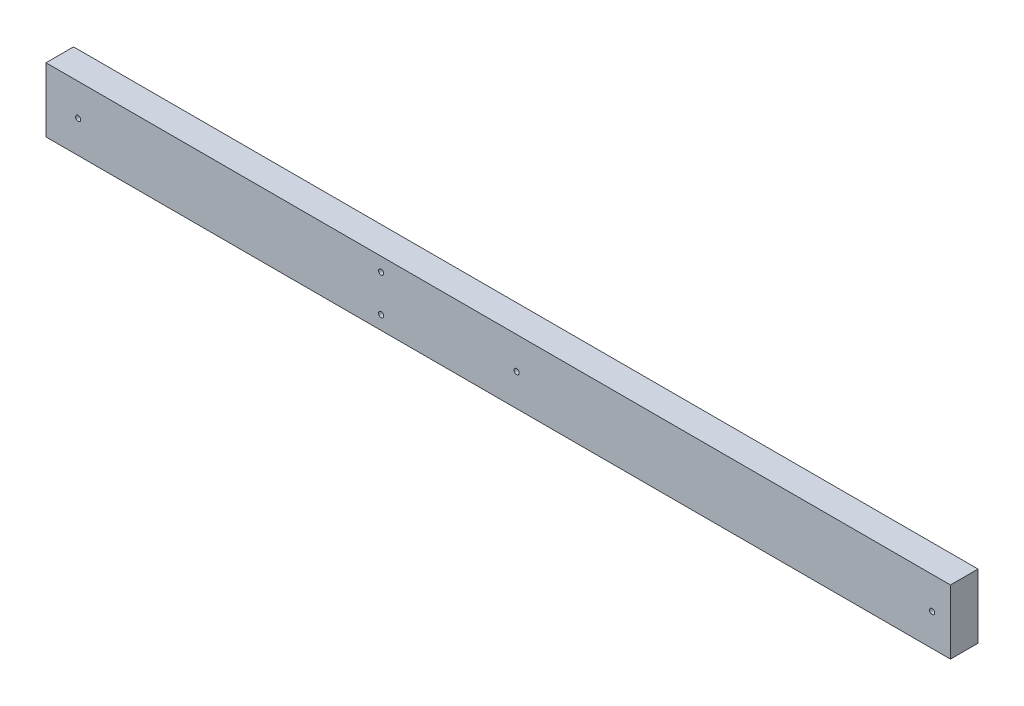
SolidWorks part; units mm, degrees
material "Pine"
ref_plane "Front Plane" through (0, 0, 0) normal (0, 0, 1) x (1, 0, 0)
ref_plane "Top Plane" through (0, 0, 0) normal (0, 1, 0) x (1, 0, 0)
ref_plane "Right Plane" through (0, 0, 0) normal (1, 0, 0) x (0, 0, -1)
sketch "Sketch1" plane through (0, 0, 0) normal (1, 0, 0) x (0, 0, -1)
  line L1 (0, 0) -> (38.1, 0)
  line L2 (0, 0) -> (0, 88.9)
  line L3 (0, 88.9) -> (38.1, 88.9)
  line L4 (38.1, 0) -> (38.1, 88.9)
  dimension "D1" = 38.1
  dimension "D2" = 88.9
extrude "Boss-Extrude1" add sketch "Sketch1" along normal blind 1250.95
sketch "Sketch2" plane through (0, 0, 0) normal (0, 0, 1) x (1, 0, 0)
  line L0 (0, 88.9) -> (0, 0) construction
  line L1 (1250.95, 88.9) -> (0, 88.9) construction
  line L2 (1250.95, 88.9) -> (1250.95, 0) construction
  line L3 (1250.95, 0) -> (0, 0) construction
  circle A0 centre (44.45, 44.45) radius 3.5719
  circle A1 centre (1225.55, 44.45) radius 3.5719
  circle A2 centre (650.875, 44.45) radius 3.5719
  circle A3 centre (463.55, 19.05) radius 3.5719
  circle A4 centre (463.55, 69.85) radius 3.5719
  dimension "D3" = 7.1437
  dimension "D5" = 7.1437
  dimension "D8" = 7.1437
  dimension "D9" = 44.45
  dimension "D12" = 7.1437
  dimension "D15" = 7.1437
  dimension "D1" = 44.45
  dimension "D2" = 44.45
  dimension "D4" = 25.4
  dimension "D6" = 44.45
  dimension "D7" = 600.075
  dimension "D10" = 463.55
  dimension "D11" = 19.05
  dimension "D13" = 19.05
  dimension "D14" = 463.55
extrude "Cut-Extrude1" cut sketch "Sketch2" against normal through all
